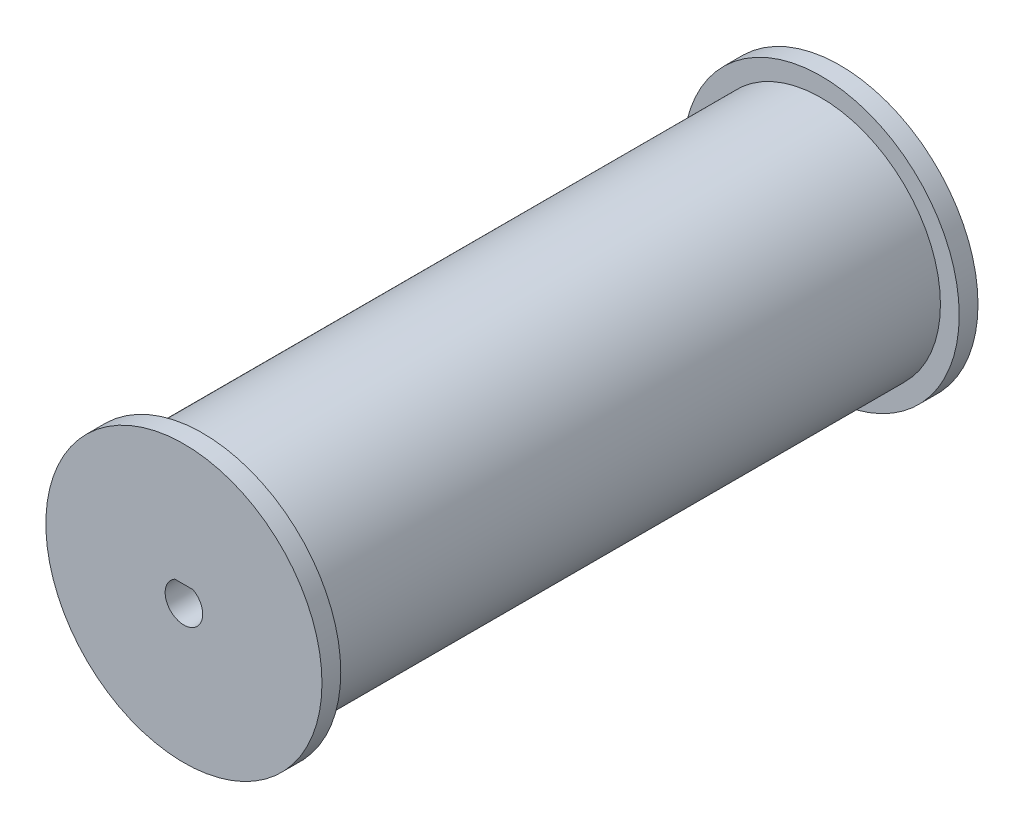
SolidWorks part; units mm, degrees
ref_plane "Front Plane" through (0, 0, 0) normal (0, 0, 1) x (1, 0, 0)
ref_plane "Top Plane" through (0, 0, 0) normal (0, 1, 0) x (1, 0, 0)
ref_plane "Right Plane" through (0, 0, 0) normal (1, 0, 0) x (0, 0, -1)
sketch "Sketch1" plane through (0, 0, 0) normal (0, 0, 1) x (1, 0, 0)
  circle A0 centre (0, 0) radius 12.7
  dimension "D1" = 25.4
extrude "Boss-Extrude1" add sketch "Sketch1" along normal blind 69.85 contours A0
sketch "Sketch2" plane through (0, 0, 69.85) normal (0, 0, 1) x (1, 0, 0)
  line L0 (0, 12.7) -> (0, -12.7) construction
  line L1 (-0.9682, 1.75) -> (0.9682, 1.75)
  circle A0 centre (0, 0) radius 12.7 construction
  arc A1 (-0.9682, 1.75) -> (0.9682, 1.75) centre (0, 0) ccw
  point P8 (0, 1.75)
  dimension "D1" = 2
  dimension "D2" = 1.75
extrude "Cut-Extrude1" cut sketch "Sketch2" against normal blind 10
sketch "Sketch3" plane through (0, 0, 0) normal (0, 0, -1) x (-1, 0, 0)
  circle A0 centre (0, 0) radius 3.572
  dimension "D1" = 7.144
extrude "Cut-Extrude2" cut sketch "Sketch3" against normal blind 34.925
sketch "Sketch5" plane through (0, 0, 0) normal (0, 0, 1) x (1, 0, 0)
  circle A0 centre (0, 0) radius 14.7
  circle A2 centre (0, 0) radius 3.572
extrude "Boss-Extrude2" add sketch "Sketch5" along normal blind 2 contours A2 | A0
sketch "Sketch8" plane through (0, 0, 0) normal (0, 0, 1) x (1, 0, 0)
  line L0 (-0.9682, 1.75) -> (0.9682, 1.75)
  circle A0 centre (0, 0) radius 14.7
  arc A1 (-0.9682, 1.75) -> (0.9682, 1.75) centre (0, 0) ccw
extrude "Boss-Extrude5" add sketch "Sketch8" against normal blind 2 from surface at 69.85 starting at face at (0, -0.125, 69.85)
